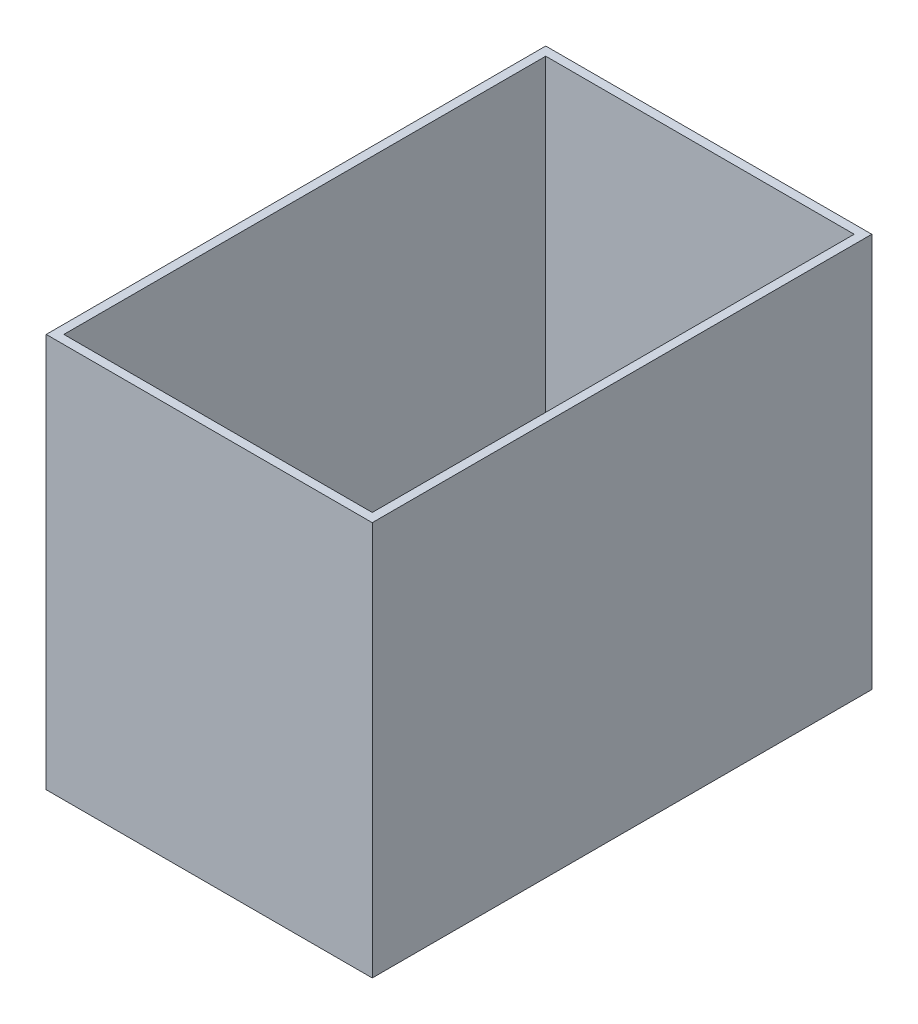
SolidWorks part; units mm, degrees
ref_plane "Front" through (0, 0, 0) normal (0, 0, 1) x (1, 0, 0)
ref_plane "Top" through (0, 0, 0) normal (0, 1, 0) x (1, 0, 0)
ref_plane "Right" through (0, 0, 0) normal (1, 0, 0) x (0, 0, -1)
sketch "Sketch1" plane through (0, 0, 0) normal (0, 1, 0) x (1, 0, 0)
  line L1 (0, 0) -> (111, 0)
  line L2 (0, 0) -> (0, -170.0625)
  line L3 (0, -170.0625) -> (111, -170.0625)
  line L4 (111, 0) -> (111, -170.0625)
  dimension "D1" = 111
  dimension "D2" = 170.0625
extrude "Boss-Extrude1" add sketch "Sketch1" along normal blind 3
sketch "Sketch2" plane through (0, 3, 0) normal (0, 1, 0) x (1, 0, 0)
  line L0 (3, -3) -> (3, -167.0625)
  line L1 (0, 0) -> (111, 0)
  line L2 (0, 0) -> (0, -170.0625)
  line L3 (0, -170.0625) -> (111, -170.0625)
  line L4 (111, 0) -> (111, -170.0625)
  line L5 (3, -167.0625) -> (108, -167.0625)
  line L6 (108, -3) -> (108, -167.0625)
  line L7 (3, -3) -> (108, -3)
  dimension "D1" = 3
extrude "Boss-Extrude2" add sketch "Sketch2" along normal blind 131.25
sketch "Sketch3" plane through (0, 0, 0) normal (0, -1, 0) x (-1, 0, 0)
  line L0 (0, -170.0625) -> (-111, -170.0625) construction
  line L1 (0, 0) -> (0, -170.0625) construction
  circle A0 centre (-55.5, -85.0312) radius 47
  dimension "D1" = 94
  dimension "D2" = 85.0312
  dimension "D3" = 55.5
extrude "Cut-Extrude1" cut sketch "Sketch3" against normal blind 3
equation "\"D1@Sketch1\"=105+6"
equation "\"D2@Sketch1\"=105*1.25*1.25+6"
equation "\"D1@Boss-Extrude2\"=105*1.25"
equation "\"D2@Sketch3\"=\"D2@Sketch1\"/2"
equation "\"D3@Sketch3\"=\"D1@Sketch1\"/2"
